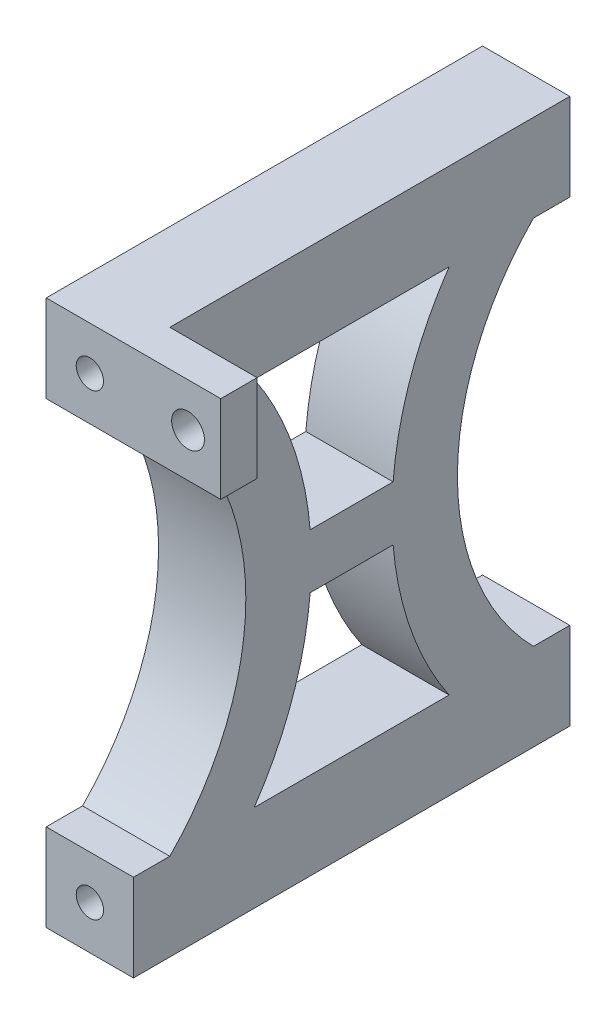
SolidWorks part; units mm, degrees
ref_plane "Front Plane" through (0, 0, 0) normal (0, 0, 1) x (1, 0, 0)
ref_plane "Top Plane" through (0, 0, 0) normal (0, 1, 0) x (1, 0, 0)
ref_plane "Right Plane" through (0, 0, 0) normal (1, 0, 0) x (0, 0, -1)
sketch "Sketch1" plane through (0, 0, 0) normal (0, 0, 1) x (1, 0, 0)
  line L0 (0, 0) -> (0, 21) construction
  line L1 (-4, 25) -> (4, 25)
  line L2 (-4, 25) -> (-4, 17)
  line L3 (-4, 17) -> (4, 17)
  line L4 (4, 25) -> (4, 17)
  line L5 (-4, 25) -> (4, 17) construction
  line L6 (-4, 17) -> (4, 25) construction
  line L7 (0, 0) -> (5.9978, 0) construction
  line L8 (-4, -17) -> (4, -25) construction
  line L9 (-4, -25) -> (4, -17) construction
  line L10 (4, -25) -> (4, -17)
  line L11 (-4, -17) -> (4, -17)
  line L12 (-4, -25) -> (-4, -17)
  line L13 (-4, -25) -> (4, -25)
  circle A0 centre (0, 21) radius 1.25
  circle A1 centre (0, -21) radius 1.25
  point P0 (0, 21)
extrude "Boss-Extrude1" add sketch "Sketch1" along normal blind 40
sketch "Sketch2" plane through (-4, 0, 0) normal (-1, 0, 0) x (0, 0, 1)
  line L0 (20, 27.6501) -> (20, -26.4609) construction
  line L1 (40, 17) -> (0, 17) construction
  line L2 (40, -17) -> (0, -17) construction
  line L3 (3.3296, 17) -> (11.064, 17)
  line L4 (3.3296, -17) -> (11.064, -17)
  line L5 (36.6704, -17) -> (28.936, -17)
  line L6 (23.8046, -2.5089) -> (16.1954, -2.5089)
  line L7 (36.6704, 17) -> (28.936, 17)
  line L8 (23.8031, 2.4911) -> (16.1969, 2.4911)
  arc A0 (3.3296, 17) -> (3.3296, -17) centre (-13.9166, 0) cw
  arc A1 (11.064, 17) -> (16.1969, 2.4911) centre (-13.9166, 0) cw
  arc A2 (16.1954, -2.5089) -> (11.064, -17) centre (-13.9166, 0) cw
  arc A3 (7.6027, 21.212) -> (7.6027, -21.212) centre (-13.9166, 0) cw construction
  arc A4 (23.8046, -2.5089) -> (28.936, -17) centre (53.9166, 0) ccw
  arc A5 (28.936, 17) -> (23.8031, 2.4911) centre (53.9166, 0) ccw
  arc A6 (36.6704, 17) -> (36.6704, -17) centre (53.9166, 0) ccw
  point P12 (20, -0.0089)
  point P22 (20, -2.5089)
  point P27 (20, 2.4911)
  dimension "D1" = 6
extrude "Boss-Extrude2" add sketch "Sketch2" against normal blind 8
sketch "Sketch3" plane through (4, 0, 0) normal (1, 0, 0) x (0, 0, -1)
  line L1 (-36.6704, 17) -> (-40, 17)
  line L2 (-36.6704, 17) -> (-36.6704, 25)
  line L3 (-36.6704, 25) -> (-40, 25)
  line L4 (-40, 17) -> (-40, 25)
extrude "Boss-Extrude3" add sketch "Sketch3" along normal blind 8
sketch "Sketch4" plane through (0, 0, 36.6704) normal (0, 0, -1) x (-1, 0, 0)
  line L0 (-12, 17) -> (-12, 25) construction
  circle A0 centre (-9, 21) radius 1.5
  dimension "D1" = 3
extrude "Cut-Extrude1" cut sketch "Sketch4" against normal blind 6
